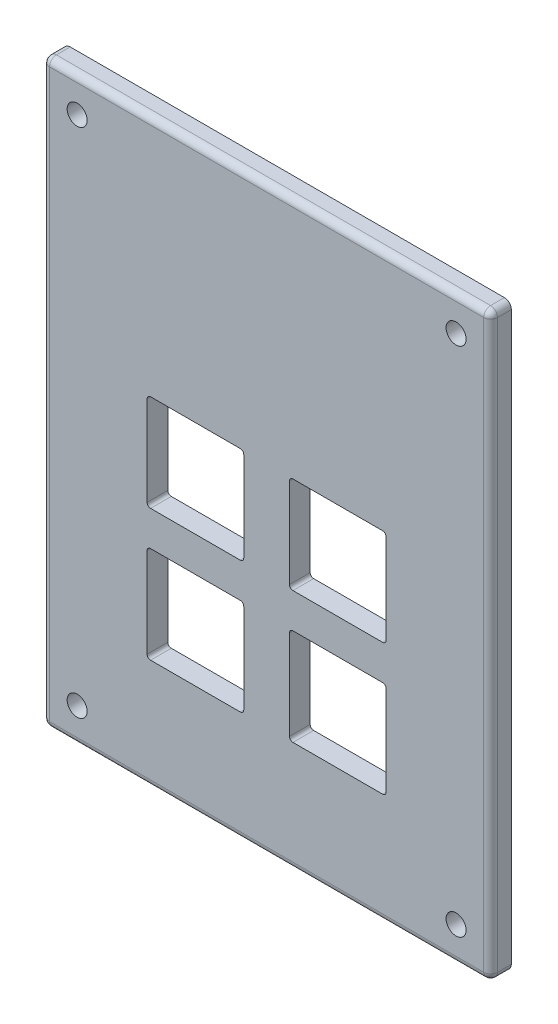
SolidWorks part; units mm, degrees
ref_plane "Front Plane" through (0, 0, 0) normal (0, 0, 1) x (1, 0, 0)
ref_plane "Top Plane" through (0, 0, 0) normal (0, 1, 0) x (1, 0, 0)
ref_plane "Right Plane" through (0, 0, 0) normal (1, 0, 0) x (0, 0, -1)
sketch "Model" plane through (0, 0, 0) normal (0, 0, 1) x (1, 0, 0)
  line L0 (3.025, -2.525) -> (16.025, -2.525)
  line L1 (3.025, -16.525) -> (16.025, -16.525)
  line L2 (2.525, -3.025) -> (2.525, -16.025)
  line L3 (16.525, -3.025) -> (16.525, -16.025)
  line L4 (23.65, -2.525) -> (36.65, -2.525)
  line L5 (23.65, -16.525) -> (36.65, -16.525)
  line L6 (23.15, -3.025) -> (23.15, -16.025)
  line L7 (37.15, -3.025) -> (37.15, -16.025)
  line L8 (3.025, -21.575) -> (16.025, -21.575)
  line L9 (3.025, -35.575) -> (16.025, -35.575)
  line L10 (2.525, -22.075) -> (2.525, -35.075)
  line L11 (16.525, -22.075) -> (16.525, -35.075)
  line L12 (23.65, -21.575) -> (36.65, -21.575)
  line L13 (23.65, -35.575) -> (36.65, -35.575)
  line L14 (23.15, -22.075) -> (23.15, -35.075)
  line L15 (37.15, -22.075) -> (37.15, -35.075)
  line L20 (-12.6125, -51.6) -> (-12.6125, 32.55)
  line L21 (-12.6125, 32.55) -> (52.2875, 32.55)
  line L22 (52.2875, 32.55) -> (52.2875, -51.6)
  line L23 (52.2875, -51.6) -> (-12.6125, -51.6)
  arc A0 (3.025, -2.525) -> (2.525, -3.025) centre (3.025, -3.025) ccw
  arc A1 (16.525, -3.025) -> (16.025, -2.525) centre (16.025, -3.025) ccw
  arc A2 (2.525, -16.025) -> (3.025, -16.525) centre (3.025, -16.025) ccw
  arc A3 (16.025, -16.525) -> (16.525, -16.025) centre (16.025, -16.025) ccw
  arc A4 (23.65, -2.525) -> (23.15, -3.025) centre (23.65, -3.025) ccw
  arc A5 (37.15, -3.025) -> (36.65, -2.525) centre (36.65, -3.025) ccw
  arc A6 (23.15, -16.025) -> (23.65, -16.525) centre (23.65, -16.025) ccw
  arc A7 (36.65, -16.525) -> (37.15, -16.025) centre (36.65, -16.025) ccw
  arc A8 (3.025, -21.575) -> (2.525, -22.075) centre (3.025, -22.075) ccw
  arc A9 (16.525, -22.075) -> (16.025, -21.575) centre (16.025, -22.075) ccw
  arc A10 (2.525, -35.075) -> (3.025, -35.575) centre (3.025, -35.075) ccw
  arc A11 (16.025, -35.575) -> (16.525, -35.075) centre (16.025, -35.075) ccw
  arc A12 (23.65, -21.575) -> (23.15, -22.075) centre (23.65, -22.075) ccw
  arc A13 (37.15, -22.075) -> (36.65, -21.575) centre (36.65, -22.075) ccw
  arc A14 (23.15, -35.075) -> (23.65, -35.575) centre (23.65, -35.075) ccw
  arc A15 (36.65, -35.575) -> (37.15, -35.075) centre (36.65, -35.075) ccw
  circle A16 centre (-7.6125, 27.55) radius 1.45
  circle A17 centre (47.2875, 27.55) radius 1.45
  circle A18 centre (47.2875, -46.6) radius 1.45
  circle A19 centre (-7.6125, -46.6) radius 1.45
  dimension "D4" = 2.9
  dimension "D7" = 2.9
  dimension "D12" = 2.9
  dimension "D13" = 2.9
  dimension "D2" = 5
  dimension "D3" = 5
  dimension "D5" = 5
  dimension "D6" = 5
  dimension "D8" = 5
  dimension "D9" = 64.9
  dimension "D10" = 84.15
  dimension "D11" = 5
extrude "Boss.-Extru.2" add sketch "Model" along normal blind 3
fillet "Congé1" radius 1 1 edges at (-12.6125, -9.525, 3)
fillet "Congé2" radius 1 1 edges at (52.2875, -9.525, 3)
fillet "Congé4" radius 1 5 edges at (-12.6125, -51.6, 1) (-12.3196, -51.6, 2.7071) (52.2875, -51.6, 1) (51.9946, -51.6, 2.7071) (19.8375, -51.6, 3)
fillet "Congé5" radius 1 5 edges at (52.2875, 32.55, 1) (51.9946, 32.55, 2.7071) (-12.6125, 32.55, 1) (-12.3196, 32.55, 2.7071) (19.8375, 32.55, 3)
